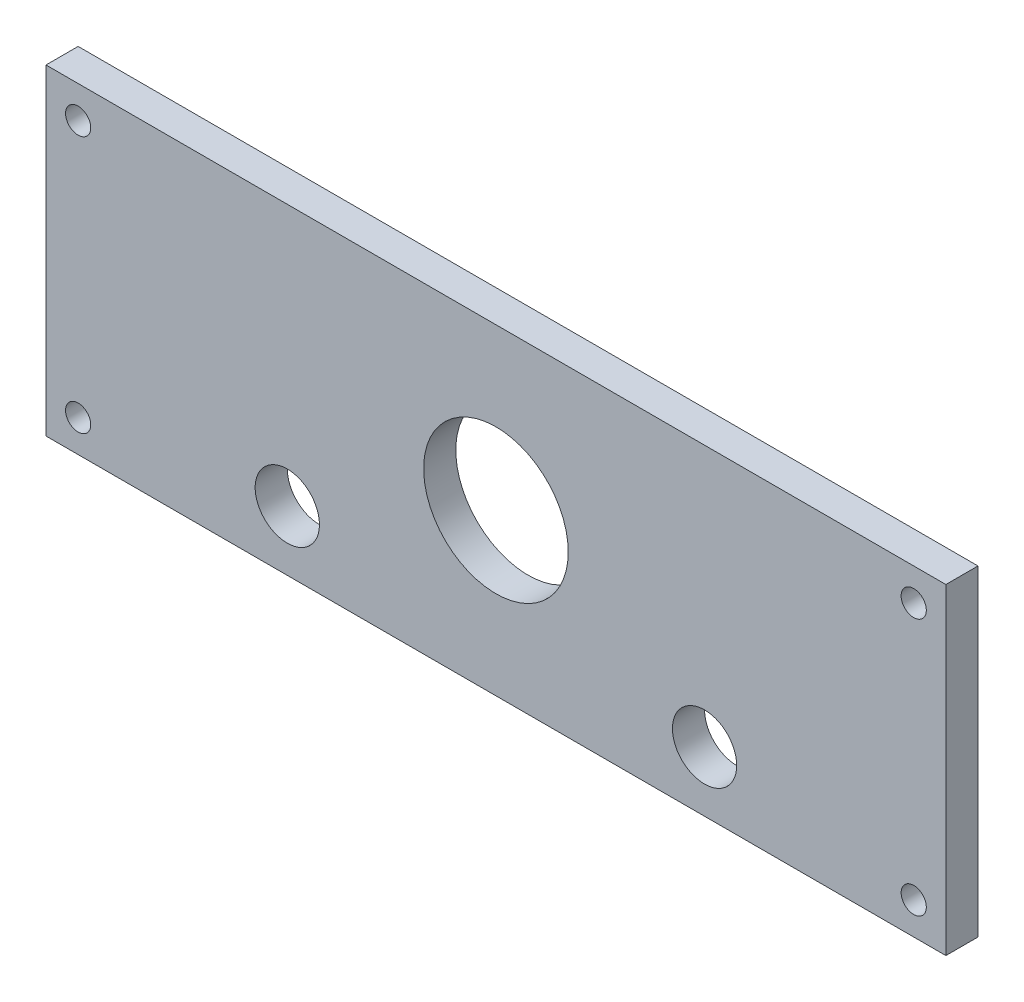
SolidWorks part; units mm, degrees
material "6061 Alloy"
ref_plane "Front Plane" through (0, 0, 0) normal (0, 0, 1) x (1, 0, 0)
ref_plane "Top Plane" through (0, 0, 0) normal (0, 1, 0) x (1, 0, 0)
ref_plane "Right Plane" through (0, 0, 0) normal (1, 0, 0) x (0, 0, -1)
sketch "Sketch1" plane through (0, 0, 0) normal (0, 0, 1) x (1, 0, 0)
  line L0 (0, 49.5808) -> (0, 0) construction
  line L1 (-41.222, 29.6882) -> (0, 49.5808) construction
  line L2 (0, 63.8683) -> (0, 127) construction
  line L3 (-52.2611, 52.5639) -> (-30.1828, 6.8125) construction
  line L4 (-127, -127) -> (127, -127) construction
  line L5 (-127, -127) -> (-127, 127) construction
  line L6 (-127, 127) -> (127, 127) construction
  line L7 (127, -127) -> (127, 127) construction
  line L8 (-127, -127) -> (127, 127) construction
  line L9 (-127, 127) -> (127, -127) construction
  line L10 (0, -14.2875) -> (0, -127) construction
  line L11 (-41.222, 29.6882) -> (0, 0) construction
  line L13 (-88.9, 17.8308) -> (88.9, 17.8308)
  line L14 (-88.9, 17.8308) -> (-88.9, 81.3308)
  line L15 (-88.9, 81.3308) -> (88.9, 81.3308)
  line L16 (88.9, 17.8308) -> (88.9, 81.3308)
  line L17 (-88.9, 17.8308) -> (88.9, 81.3308) construction
  line L18 (-88.9, 81.3308) -> (88.9, 17.8308) construction
  circle A0 centre (0, 0) radius 114.3 construction
  circle A1 centre (0, 0) radius 38.1 construction
  circle A2 centre (0, 49.5808) radius 11.43 construction
  circle A3 centre (0, 49.5808) radius 38.1 construction
  circle A4 centre (-41.222, 29.6882) radius 7.62 construction
  circle A6 centre (-41.222, 29.6882) radius 6.35
  circle A8 centre (-41.222, 29.6882) radius 25.4 construction
  circle A9 centre (-41.222, 29.6882) radius 33.02 construction
  circle A12 centre (-41.222, 29.6882) radius 8.89 construction
  circle A13 centre (0, 0) radius 39.37 construction
  circle A14 centre (0, 49.5808) radius 14.2875
  circle A15 centre (0, 0) radius 127 construction
  circle A16 centre (-98.7828, 98.7828) radius 12.7 construction
  circle A17 centre (-98.7828, 98.7828) radius 6.35 construction
  circle A18 centre (0, 0) radius 14.2875 construction
  circle A19 centre (-98.7828, -98.7828) radius 12.7 construction
  circle A20 centre (-98.7828, -98.7828) radius 6.35 construction
  circle A21 centre (0, 49.5808) radius 39.37 construction
  circle A22 centre (0, 49.5808) radius 12.7 construction
  circle A23 centre (41.222, 29.6882) radius 6.35
  circle A24 centre (-82.55, 74.9808) radius 6.35 construction
  circle A25 centre (82.55, 74.9808) radius 6.35 construction
  circle A26 centre (82.55, 24.1808) radius 6.35 construction
  circle A27 centre (-82.55, 24.1808) radius 6.35 construction
  point P24 (-41.222, 29.6882)
  point P27 (-98.7828, 98.7828)
  point P32 (-98.7828, -98.7828)
  point P33 (-52.2611, 52.5639)
  point P34 (-30.1828, 6.8125)
  point P40 (52.2611, 52.5639)
  point P41 (30.1828, 6.8125)
  point P42 (98.7828, -98.7828)
  point P43 (98.7828, 98.7828)
  point P58 (0, 0)
  point P59 (82.55, 24.1808)
  point P60 (-82.55, 24.1808)
  point P61 (-82.55, 74.9808)
  point P62 (0, 0)
  point P63 (0, 0)
  point P64 (0, 0)
  point P65 (82.55, 74.9808)
  point P66 (0, 0)
  point P67 (0, 0)
  dimension "D1" = 228.6
  dimension "D2" = 76.2
  dimension "D3" = 22.86
  dimension "D5" = 76.2
  dimension "D6" = 15.24
  dimension "D7" = 28.575
  dimension "D8" = 12.7
  dimension "D9" = 25.4
  dimension "D12" = 66.04
  dimension "D13" = 28.575
  dimension "D14" = 50.8
  dimension "D15" = 25.4
  dimension "D18" = 78.74
  dimension "D19" = 17.78
  dimension "D11" = 12.7
  dimension "D20" = 12.7
  dimension "D21" = 78.74
  dimension "D22" = 25.4
  dimension "D26" = 12.7
  dimension "D27" = 12.7
  dimension "D28" = 12.7
  dimension "D29" = 12.7
  dimension "D4" = 49.5808
  dimension "D10" = 45.7708
  dimension "D16" = 254
  dimension "D17" = 254
  dimension "D23" = 50.8
  dimension "D24" = 177.8
  dimension "D25" = 63.5
extrude "Boss-Extrude2" add sketch "Sketch1" along normal blind 6.35 contours L4 L7 L6 L5 A6 A14 A18 A23
hole_wizard "#9 (0.196) Diameter Hole1" positions "Sketch4" profile "Sketch5" hole size "#9" standard "ANSI Inch" end condition through all
sketch "Sketch4" plane through (0, 0, 0) normal (0, 0, -1) x (-1, 0, 0)
  point P0 (-82.55, 74.9808)
  point P3 (-82.55, 24.1808)
  point P6 (82.55, 24.1808)
  point P9 (82.55, 74.9808)
sketch "Sketch5" plane through (82.55, 74.9808, 0) normal (1, 0, 0) x (0, 1, 0)
  line L0 (0, 0) -> (0, 6.35)
  line L1 (0, 6.35) -> (2.4892, 6.35)
  line L2 (2.4892, 6.35) -> (2.4892, 0)
  line L5 (2.4892, 0) -> (0, 0)
  line L11 (0, -6.35) -> (0, 107.95) construction
  dimension "Thru Hole Dia." = 4.9784
  dimension "Thru Hole Depth" = 6.35
